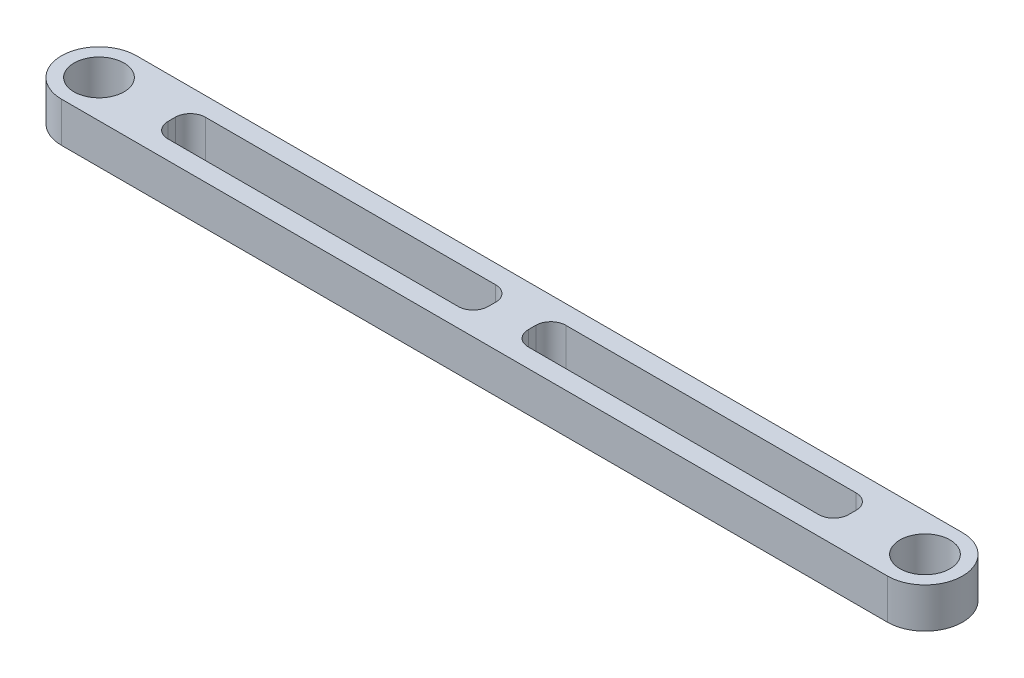
SolidWorks part; units mm, degrees
material "6061 合金"
ref_plane "前视基准面" through (0, 0, 0) normal (0, 0, 1) x (1, 0, 0)
ref_plane "上视基准面" through (0, 0, 0) normal (0, 1, 0) x (1, 0, 0)
ref_plane "右视基准面" through (0, 0, 0) normal (1, 0, 0) x (0, 0, -1)
sketch "草图1" plane through (0, 0, 0) normal (0, 1, 0) x (1, 0, 0)
  line L0 (0, 0) -> (165, 0) construction
  line L1 (0, 7.5) -> (165, 7.5)
  line L2 (0, -7.5) -> (165, -7.5)
  line L3 (82.5, -7.5) -> (82.5, 7.5) construction
  line L4 (150.5, -3.75) -> (86.5, -3.75)
  line L5 (14.5, 3.75) -> (78.5, 3.75)
  line L6 (14.5, 3.75) -> (14.5, -3.75)
  line L7 (14.5, -3.75) -> (78.5, -3.75)
  line L8 (78.5, 3.75) -> (78.5, -3.75)
  line L9 (14.5, 3.75) -> (78.5, -3.75) construction
  line L10 (14.5, -3.75) -> (78.5, 3.75) construction
  line L11 (86.5, 3.75) -> (86.5, -3.75)
  line L12 (150.5, 3.75) -> (86.5, 3.75)
  line L13 (150.5, 3.75) -> (150.5, -3.75)
  circle A0 centre (0, 0) radius 5
  circle A1 centre (0, 0) radius 7.5
  circle A2 centre (165, 0) radius 5
  circle A3 centre (165, 0) radius 7.5
  point P9 (46.5, 0)
  dimension "D2" = 15
  dimension "D3" = 10
  dimension "D4" = 10
  dimension "D5" = 15
  dimension "D1" = 165
  dimension "D6" = 7.5
  dimension "D7" = 64
  dimension "D8" = 4
extrude "凸台-拉伸1" add sketch "草图1" along normal blind 8 contours A3 L1 A1 L2 L5 L8 L7 L6 L12 L13 L4 L11 | A1 A0 | A3 A2
fillet "圆角1" radius 3 8 edges at (150.5, 4, 3.75) (150.5, 4, -3.75) (86.5, 4, 3.75) (86.5, 4, -3.75) (78.5, 4, 3.75) (78.5, 4, -3.75) (14.5, 4, -3.75) (14.5, 4, 3.75)
